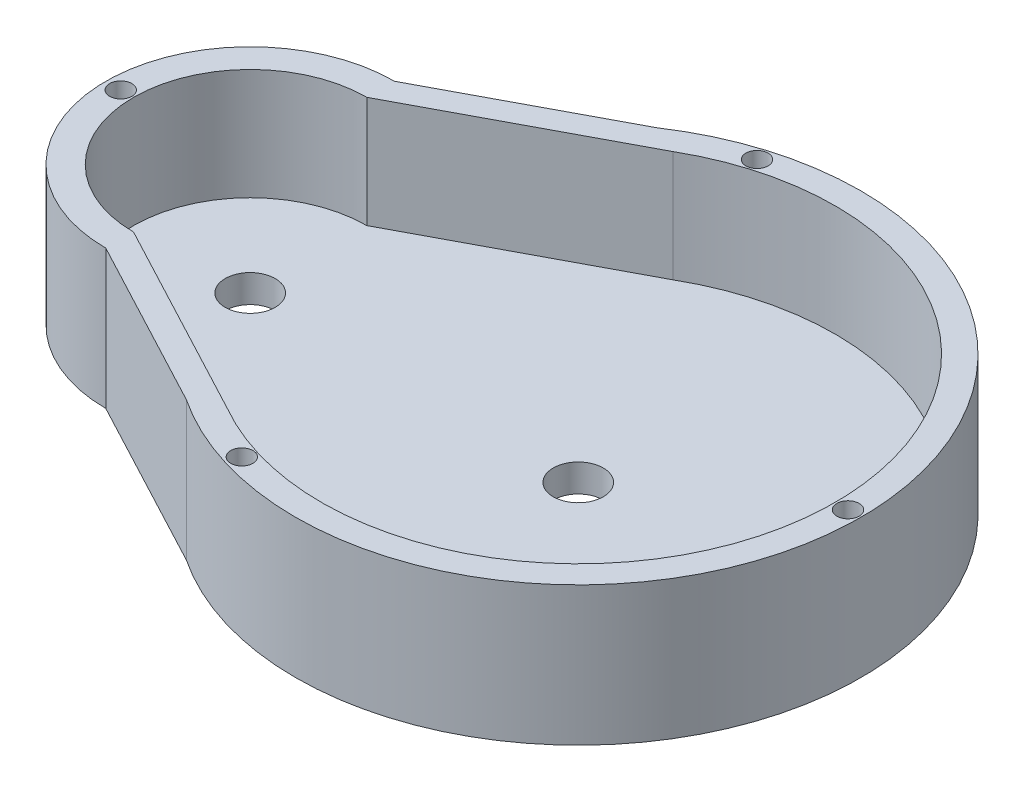
SolidWorks part; units mm, degrees
ref_plane "Front Plane" through (0, 0, 0) normal (0, 0, 1) x (1, 0, 0)
ref_plane "Top Plane" through (0, 0, 0) normal (0, 1, 0) x (1, 0, 0)
ref_plane "Right Plane" through (0, 0, 0) normal (1, 0, 0) x (0, 0, -1)
sketch "Sketch2" plane through (0, 0, 0) normal (0, 1, 0) x (1, 0, 0)
  line L0 (0, 26) -> (30.8523, 42.3604)
  line L1 (0, -26) -> (30.8523, -42.3604)
  line L2 (0, 21) -> (33.849, 36.7093)
  line L3 (0, -21) -> (30.8523, -34.4606)
  circle A1 centre (59.055, 0) radius 44.53
  circle A2 centre (0, 0) radius 4.5
  circle A3 centre (59.055, 0) radius 4.5
  circle A5 centre (59.055, 0) radius 50.89
  arc A6 (0, -26) -> (0, 26) centre (0, 0) cw
  arc A7 (0, 21) -> (0, -21) centre (0, 0) ccw
  dimension "D1" = 59.055
  dimension "D2" = 101.78
  dimension "D3" = 89.06
  dimension "D4" = 26
  dimension "D5" = 30.8523
  dimension "D6" = 30.8523
extrude "Boss-Extrude1" add sketch "Sketch2" along normal blind 5
sketch "Sketch3" plane through (0, 5, 0) normal (0, 1, 0) x (1, 0, 0)
  line L0 (0, 26) -> (30.8523, 42.3604)
  line L1 (0, -26) -> (30.8523, -42.3604)
  line L2 (0, 21) -> (35.9898, 40.0847)
  line L3 (0, -21) -> (35.9898, -40.0847)
  circle A1 centre (59.055, 0) radius 50.89
  circle A3 centre (59.055, 0) radius 46.247
  arc A4 (0, 26) -> (0, -26) centre (0, 0) ccw
  arc A6 (0, 21) -> (0, -21) centre (0, 0) ccw
  arc A7 (0, 26) -> (0, -26) centre (0, 0) ccw construction
  dimension "D1" = 0
extrude "Boss-Extrude4" add sketch "Sketch3" along normal blind 20
sketch "Sketch4" plane through (0, 25, 0) normal (0, 1, 0) x (1, 0, 0)
  circle A0 centre (-23.3, 0) radius 2
  arc A1 (0, 21) -> (0, -21) centre (0, 0) ccw construction
  circle A2 centre (107.605, 0) radius 2
  arc A3 (35.9898, -40.0847) -> (35.9898, 40.0847) centre (59.055, 0) ccw construction
  circle A4 centre (44.8118, 46.4229) radius 2
  circle A5 centre (44.8118, -46.317) radius 2
  point P5 (-21, 0)
  dimension "D1" = 2.3
  dimension "D2" = 48.55
extrude "Cut-Extrude1" cut sketch "Sketch4" against normal blind 40
sketch "Sketch5" plane through (0, 32.5573, 0) normal (0, 1, 0) x (1, 0, 0)
